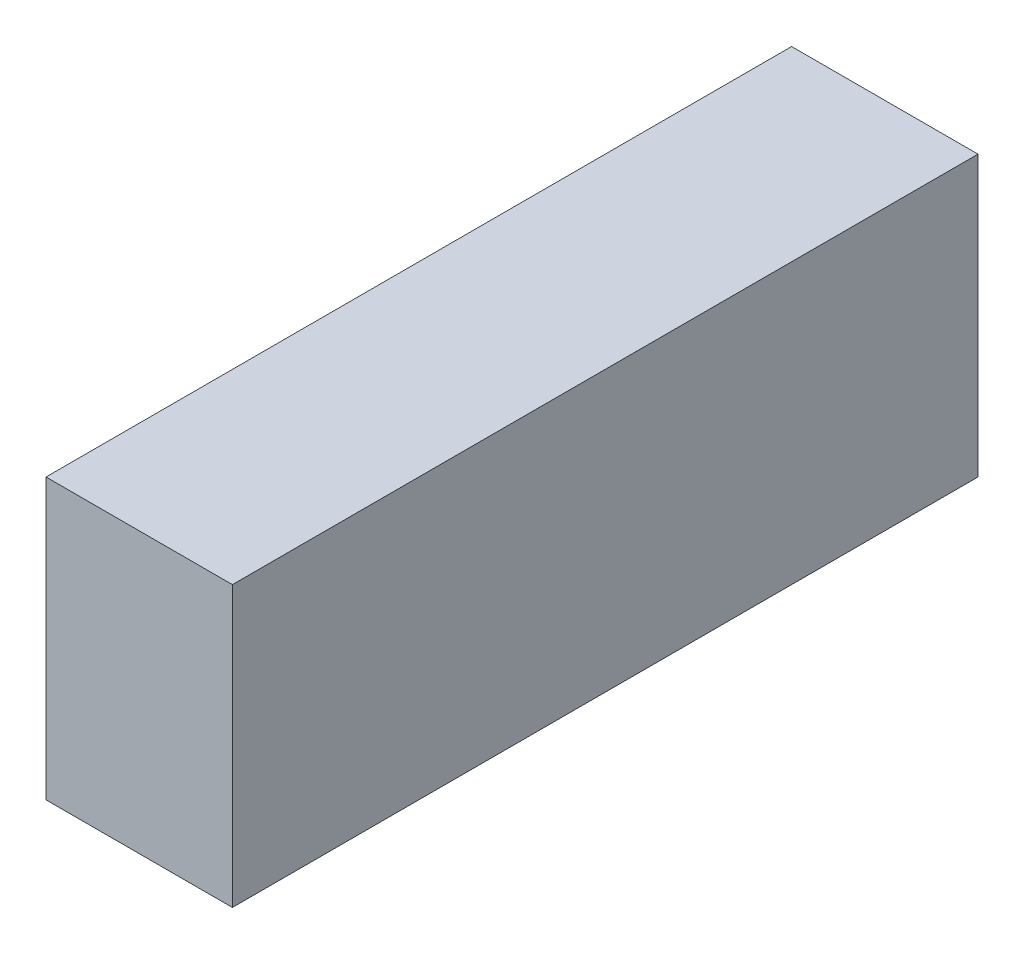
SolidWorks part; units mm, degrees
ref_plane "Front Plane" through (0, 0, 0) normal (0, 0, 1) x (1, 0, 0)
ref_plane "Top Plane" through (0, 0, 0) normal (0, 1, 0) x (1, 0, 0)
ref_plane "Right Plane" through (0, 0, 0) normal (1, 0, 0) x (0, 0, -1)
other "Configuration Table"
sketch "Sketch1" plane through (0, 0, 0) normal (0, 0, 1) x (1, 0, 0)
  line L1 (2, 33) -> (12, 33)
  line L2 (2, 33) -> (2, 48)
  line L3 (2, 48) -> (12, 48)
  line L4 (12, 33) -> (12, 48)
extrude "CEK_taze_kayis_baglanti_pabucu_1" add sketch "Sketch1" against normal blind 40 from offset 40 separate body
